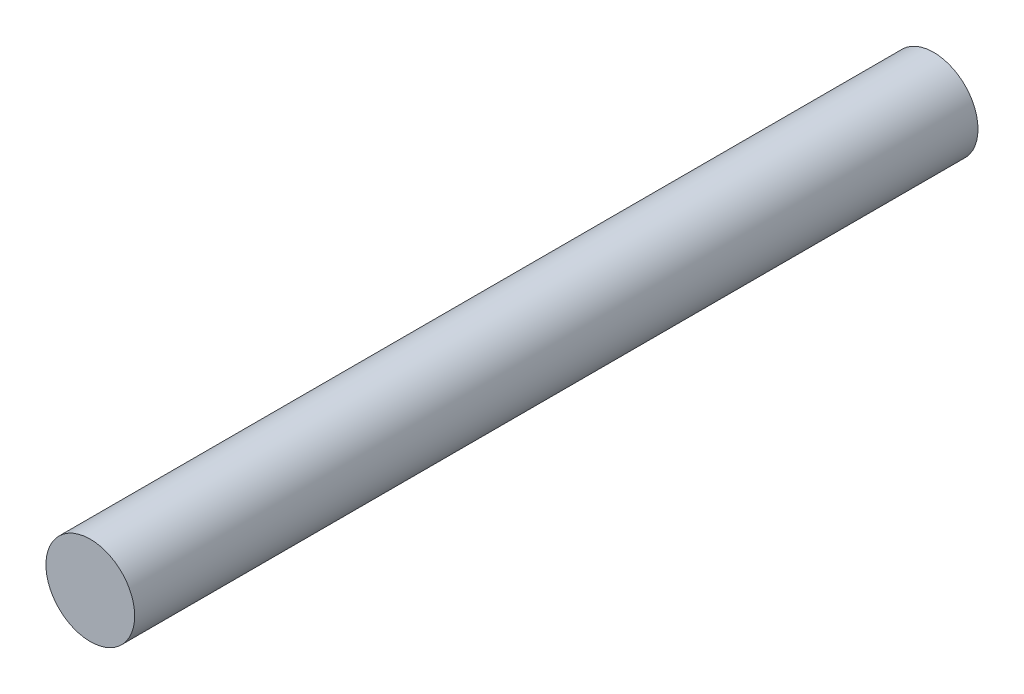
SolidWorks part; units mm, degrees
material "ｽﾃﾝﾚｽ鋼(ｸﾛﾑ)"
ref_plane "正面" through (0, 0, 0) normal (0, 0, 1) x (1, 0, 0)
ref_plane "平面" through (0, 0, 0) normal (0, 1, 0) x (1, 0, 0)
ref_plane "右側面" through (0, 0, 0) normal (1, 0, 0) x (0, 0, -1)
sketch "ｽｹｯﾁ1" plane through (0, 0, 0) normal (0, 0, 1) x (1, 0, 0)
  circle A0 centre (0, 0) radius 2
  dimension "D1" = 4
extrude "ﾎﾞｽ - 押し出し1" add sketch "ｽｹｯﾁ1" along normal blind 38
